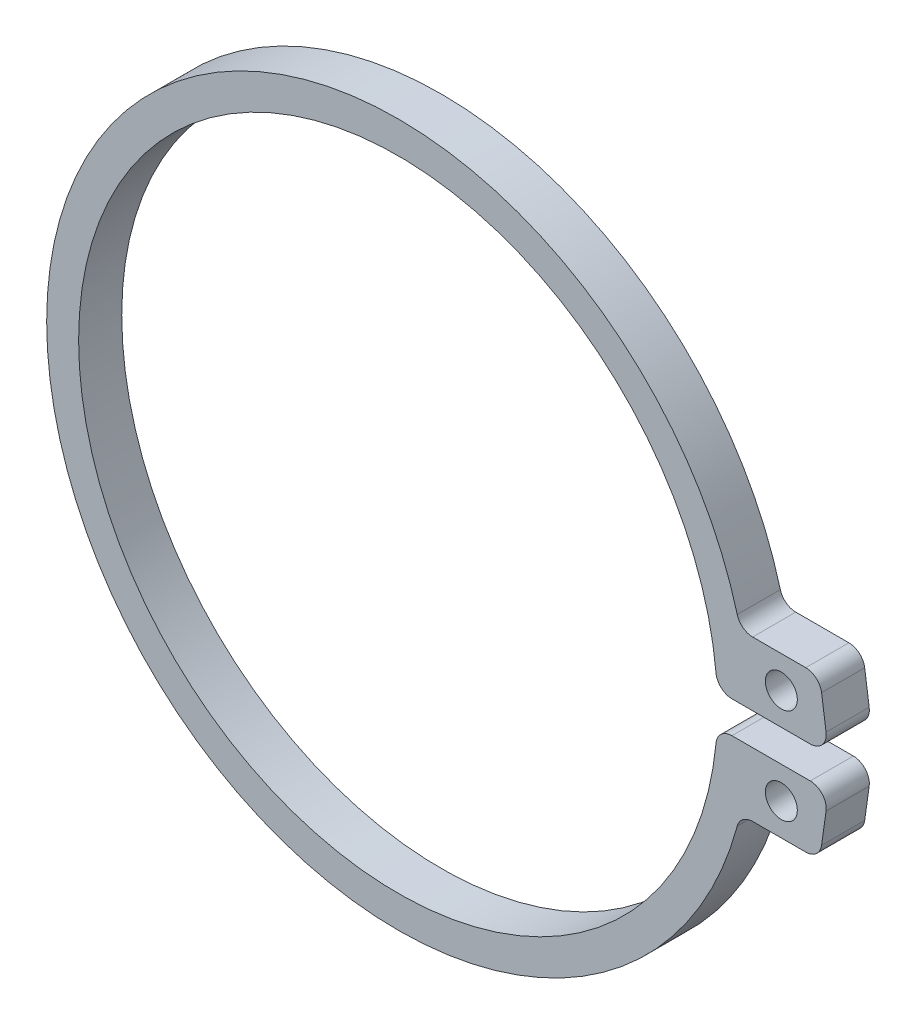
SolidWorks part; units mm, degrees
ref_plane "Front Plane" through (0, 0, 0) normal (1, 0, 0) x (0, 1, 0)
ref_plane "Top Plane" through (0, 0, 0) normal (0, 0, 1) x (0, 1, 0)
ref_plane "Right Plane" through (0, 0, 0) normal (0, 1, 0) x (-1, 0, 0)
sketch "Sketch1" plane through (0, 0, 0) normal (0, 0, 1) x (0, 1, 0)
  line L0 (-5.2462, 0) -> (5.2462, 0) construction
  line L1 (0, 3.8461) -> (0, -7.0518) construction
  line L2 (-0.5, -10.4523) -> (-0.5, -12.9049)
  line L3 (1.0696, -13.4) -> (2.0696, -13.2595)
  line L4 (-2.5, -11.1018) -> (-2.5, -12.7643)
  line L6 (-1.0696, -13.4) -> (-2.0696, -13.2595)
  line L7 (2.5, -11.1018) -> (2.5, -12.7643)
  line L8 (0.5, -12.9049) -> (0.5, -10.4523)
  arc A0 (0.9524, -9.9545) -> (-0.9524, -9.9545) centre (0, 0) ccw
  arc A1 (2.8696, -10.6191) -> (-2.8696, -10.6191) centre (0, 0) ccw
  circle A2 centre (-1.5, -12) radius 0.5
  circle A3 centre (1.5, -12) radius 0.5
  arc A4 (1.0696, -13.4) -> (0.5, -12.9049) centre (1, -12.9049) cw
  arc A5 (-1.0696, -13.4) -> (-0.5, -12.9049) centre (-1, -12.9049) ccw
  arc A6 (2.0696, -13.2595) -> (2.5, -12.7643) centre (2, -12.7643) ccw
  arc A7 (-2.5, -12.7643) -> (-2.0696, -13.2595) centre (-2, -12.7643) ccw
  arc A8 (0.9524, -9.9545) -> (0.5, -10.4523) centre (1, -10.4523) ccw
  arc A9 (-0.5, -10.4523) -> (-0.9524, -9.9545) centre (-1, -10.4523) ccw
  arc A10 (2.5, -11.1018) -> (2.8696, -10.6191) centre (3, -11.1018) cw
  arc A11 (-2.5, -11.1018) -> (-2.8696, -10.6191) centre (-3, -11.1018) ccw
  dimension "D4" = 2
  dimension "D5" = 1
  dimension "D1" = 82
  dimension "D2" = 3
  dimension "D3" = 2
  dimension "D10" = 10
  dimension "D11" = 11
  dimension "D12" = 1
  dimension "D13" = 0.5
  dimension "D14" = 0.5
  dimension "D15" = 0.5
  dimension "D6" = 3
  dimension "D7" = 2
  dimension "D8" = 1.4
  dimension "D9" = 12
extrude "Boss-Extrude1" add sketch "Sketch1" along normal mid plane 1.35
